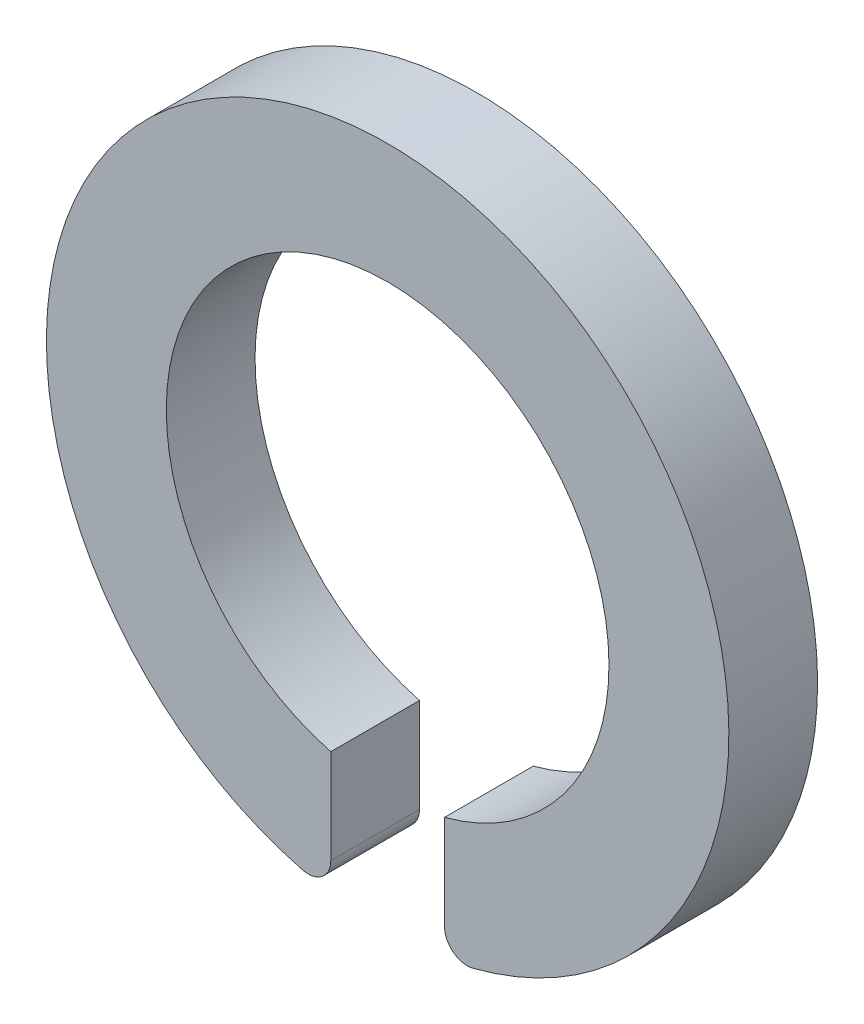
SolidWorks part; units mm, degrees
ref_plane "Front Plane" through (0, 0, 0) normal (0, 0, 1) x (1, 0, 0)
ref_plane "Top Plane" through (0, 0, 0) normal (0, 1, 0) x (1, 0, 0)
ref_plane "Right Plane" through (0, 0, 0) normal (1, 0, 0) x (0, 0, -1)
sketch "Sketch1" plane through (0, 0, 0) normal (0, 0, 1) x (1, 0, 0)
  circle A0 centre (0, 0) radius 4.865
  circle A1 centre (0, 0) radius 7.5
  dimension "D1" = 9.73
  dimension "D2" = 15
extrude "Boss-Extrude1" add sketch "Sketch1" along normal blind 1.95
sketch "Sketch2" plane through (0, 0, 1.95) normal (0, 0, 1) x (1, 0, 0)
  line L0 (0, 0) -> (0, -1.4163) construction
  line L1 (-1.25, -3.7678) -> (1.25, -3.7678)
  line L2 (-1.25, -3.7678) -> (-1.25, -8.7359)
  line L3 (-1.25, -8.7359) -> (1.25, -8.7359)
  line L4 (1.25, -3.7678) -> (1.25, -8.7359)
  dimension "D1" = 2.5
extrude "Cut-Extrude1" cut sketch "Sketch2" against normal through all
fillet "Fillet1" radius 0.5 2 edges at (1.25, -7.3951, 0.975) (-1.25, -7.3951, 0.975)
equation "\"D1@Sketch1\"=9.53+.2"
